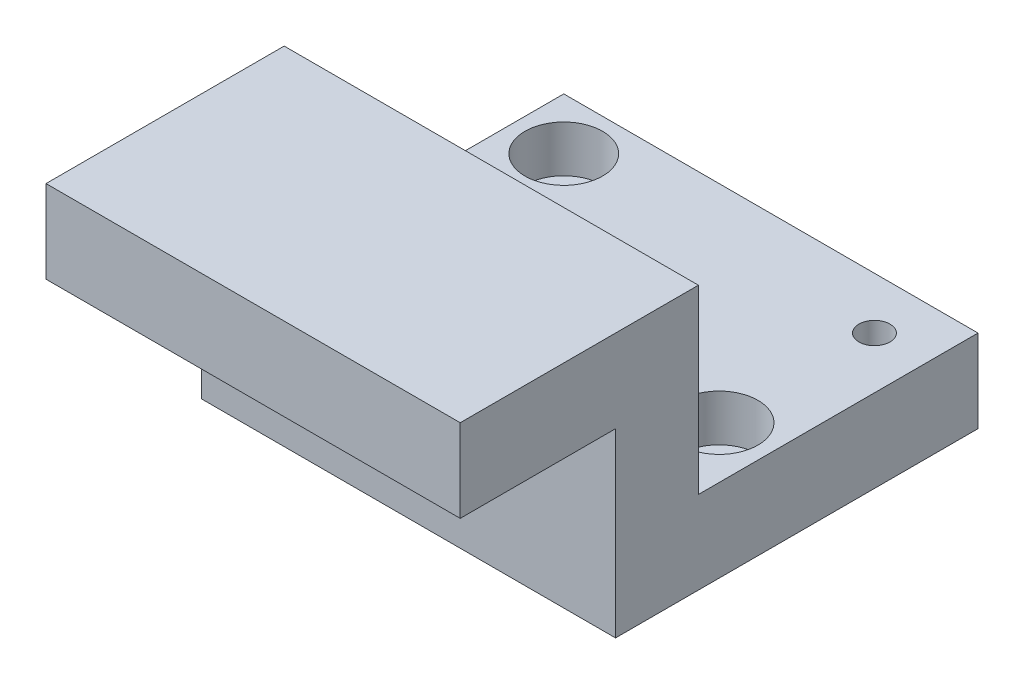
SolidWorks part; units mm, degrees
material "Q235A"
ref_plane "前视" through (0, 0, 0) normal (0, 0, 1) x (1, 0, 0)
ref_plane "上视" through (0, 0, 0) normal (0, 1, 0) x (1, 0, 0)
ref_plane "右视" through (0, 0, 0) normal (1, 0, 0) x (0, 0, -1)
sketch "草图1" plane through (0, 0, 0) normal (0, 0, 1) x (1, 0, 0)
  line L1 (40, -25.5) -> (-40, -25.5)
  line L2 (40, -25.5) -> (40, 25.5)
  line L3 (40, 25.5) -> (-40, 25.5)
  line L4 (-40, -25.5) -> (-40, 25.5)
  line L5 (40, -25.5) -> (-40, 25.5) construction
  line L6 (40, 25.5) -> (-40, -25.5) construction
  point P0 (0, 0)
  dimension "D1" = 51
  dimension "D2" = 80
extrude "凸台-拉伸1" add sketch "草图1" along normal blind 100
sketch "草图2" plane through (40, 0, 0) normal (1, 0, 0) x (0, 0, -1)
  line L0 (-100, 25.5) -> (0, 25.5) construction
  line L1 (-100, -25.5) -> (-70, -25.5)
  line L2 (-100, -25.5) -> (-100, 9.5)
  line L3 (-100, 9.5) -> (-70, 9.5)
  line L4 (-70, -25.5) -> (-70, 9.5)
  dimension "D1" = 30
  dimension "D2" = 16
extrude "切除-拉伸1" cut sketch "草图2" against normal through all
sketch "草图3" plane through (40, 0, 0) normal (1, 0, 0) x (0, 0, -1)
  line L0 (-70, -25.5) -> (-70, 9.5) construction
  line L1 (0, 25.5) -> (-54, 25.5)
  line L2 (0, 25.5) -> (0, -9.5)
  line L3 (0, -9.5) -> (-54, -9.5)
  line L4 (-54, 25.5) -> (-54, -9.5)
  line L5 (-70, -25.5) -> (0, -25.5) construction
  dimension "D1" = 16
  dimension "D2" = 16
extrude "切除-拉伸2" cut sketch "草图3" against normal through all
hole_wizard "打孔尺寸(%根据)内六角圆柱头螺钉的类型1" positions "草图6" profile "草图4" counterbore size "M8" standard "GB" end condition through all
sketch "草图6" plane through (0, -9.5, 0) normal (0, 1, 0) x (1, 0, 0)
  line L0 (-40, -54) -> (-40, 0) construction
  line L1 (-40, 0) -> (40, 0) construction
  line L2 (40, -54) -> (40, 0) construction
  point P0 (-30, -10)
  point P2 (30, -40)
  dimension "D1" = 10
  dimension "D2" = 10
  dimension "D3" = 10
  dimension "D4" = 30
sketch "草图4" plane through (-30, -9.5, 10) normal (1, 0, 0) x (0, 0, 1)
  line L0 (0, 0) -> (0, 16)
  line L1 (0, 16) -> (4.5, 16)
  line L3 (4.5, 16) -> (4.5, 9)
  line L4 (4.5, 9) -> (7.5, 9)
  line L5 (7.5, 9) -> (7.5, 0)
  line L7 (7.5, 0) -> (0, 0)
  line L11 (0, -6.35) -> (0, 107.95) construction
  dimension "通孔孔直径" = 9
  dimension "通孔孔深度" = 16
  dimension "柱形沉头孔直径" = 15
  dimension "柱形沉头孔深度" = 9
hole_wizard "大小mm 暗销孔1" positions "草图8" profile "草图7" hole size "Ø6.0" standard "GB" end condition through all
sketch "草图8" plane through (0, -9.5, 0) normal (0, 1, 0) x (1, 0, 0)
  line L0 (-30, -10) -> (30, -10) construction
  line L2 (-30, -10) -> (-30, -40) construction
  line L3 (-30, -40) -> (30, -40) construction
  line L4 (30, -40) -> (30, -10) construction
  point P0 (-30, -40)
  point P2 (30, -10)
sketch "草图7" plane through (-30, -9.5, 40) normal (1, 0, 0) x (0, 0, 1)
  line L0 (0, 0) -> (0, 16)
  line L1 (0, 16) -> (3, 16)
  line L2 (3, 16) -> (3, 0)
  line L5 (3, 0) -> (0, 0)
  line L11 (0, -6.35) -> (0, 107.95) construction
  dimension "通孔孔直径" = 6
  dimension "通孔孔深度" = 16
